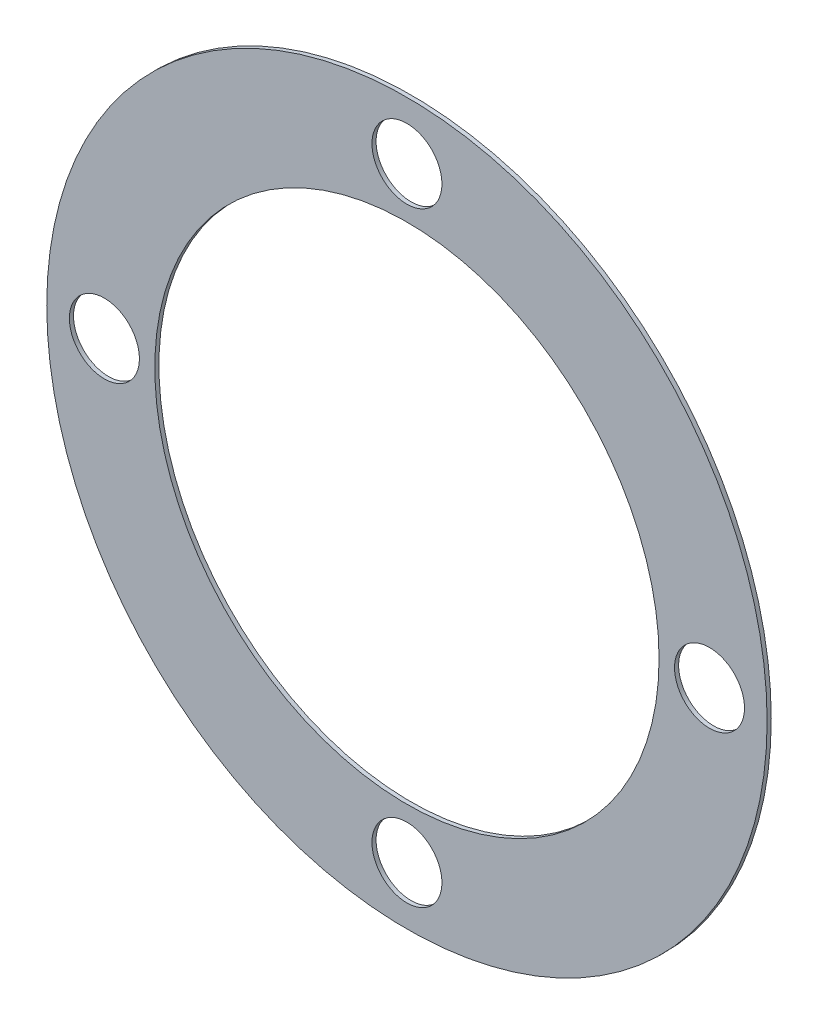
SolidWorks part; units mm, degrees
material "TESNIT BA-R"
ref_plane "Front Plane" through (0, 0, 0) normal (0, 0, 1) x (1, 0, 0)
ref_plane "Top Plane" through (0, 0, 0) normal (0, 1, 0) x (1, 0, 0)
ref_plane "Right Plane" through (0, 0, 0) normal (1, 0, 0) x (0, 0, -1)
sketch "Sketch1" plane through (0, 0, 0) normal (0, 0, 1) x (1, 0, 0)
  line L0 (0, 0) -> (98.7121, 0) construction
  line L1 (0, 0) -> (0, 77.0142) construction
  circle A0 centre (0, 0) radius 87.5
  circle A1 centre (0, 73.5) radius 8.5
  circle A2 centre (73.5, 0) radius 8.5
  circle A3 centre (0, 0) radius 73.5 construction
  circle A4 centre (-73.5, 0) radius 8.5
  circle A5 centre (0, -73.5) radius 8.5
  circle A6 centre (0, 0) radius 61.25
  dimension "D1" = 175
  dimension "D2" = 17
  dimension "D3" = 147
  dimension "D4" = 122.5
extrude "Boss-Extrude1" add sketch "Sketch1" along normal blind 1
